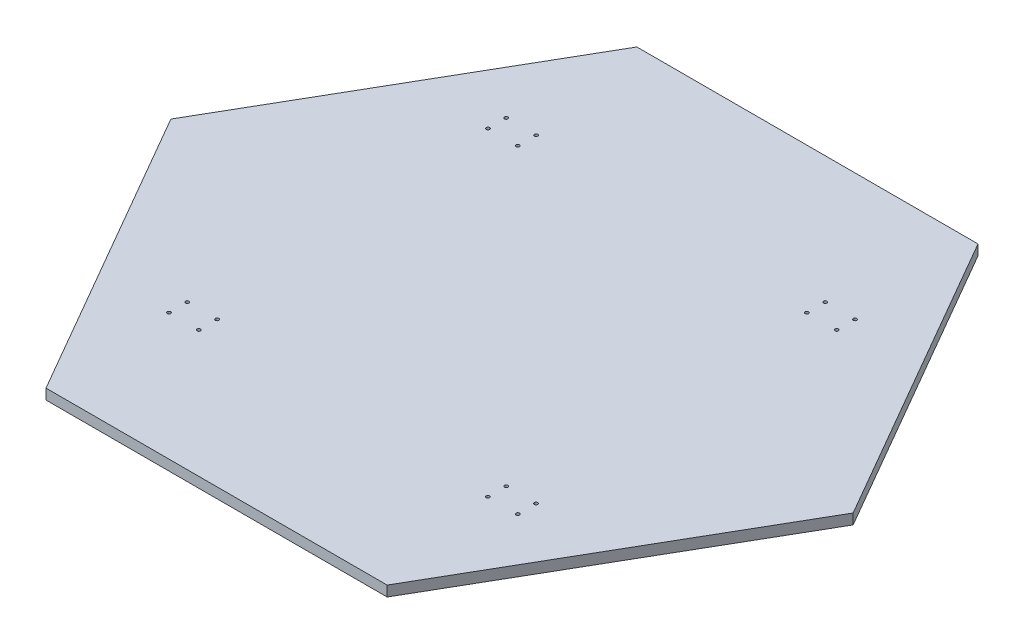
SolidWorks part; units mm, degrees
ref_plane "Front Plane" through (0, 0, 0) normal (0, 0, 1) x (1, 0, 0)
ref_plane "Top Plane" through (0, 0, 0) normal (0, 1, 0) x (1, 0, 0)
ref_plane "Right Plane" through (0, 0, 0) normal (1, 0, 0) x (0, 0, -1)
sketch "Sketch1" plane through (0, 0, 0) normal (0, 1, 0) x (1, 0, 0)
  line L38 (835.3235, 0) -> (417.6617, 723.4114)
  line L39 (417.6617, 723.4114) -> (-417.6617, 723.4114)
  line L40 (-417.6617, 723.4114) -> (-835.3235, 0)
  line L41 (-835.3235, 0) -> (-417.6617, -723.4114)
  line L42 (-417.6617, -723.4114) -> (417.6617, -723.4114)
  line L43 (417.6617, -723.4114) -> (835.3235, 0)
  line L44 (762, 0) -> (381, 659.9114)
  line L45 (381, 659.9114) -> (-381, 659.9114)
  line L46 (-381, 659.9114) -> (-762, 0)
  line L47 (-762, 0) -> (-381, -659.9114)
  line L48 (-381, -659.9114) -> (381, -659.9114)
  line L49 (381, -659.9114) -> (762, 0)
  line L50 (762, 0) -> (381, 659.9114) construction
  line L51 (381, 659.9114) -> (-381, 659.9114) construction
  line L52 (-381, 659.9114) -> (-762, 0) construction
  line L53 (-762, 0) -> (-381, -659.9114) construction
  line L54 (-381, -659.9114) -> (381, -659.9114) construction
  line L55 (381, -659.9114) -> (762, 0) construction
  point P1 (923.3117, 0)
  dimension "D1" = 0
  dimension "D2" = 63.5
extrude "Boss-Extrude1" add sketch "Sketch1" along normal blind 25.4
sketch "Sketch5" plane through (0, 25.4, 0) normal (0, 1, 0) x (1, 0, 0)
  line L0 (-390.525, 390.525) -> (390.525, 390.525) construction
  line L1 (-427.101, 412.877) -> (-353.949, 412.877) construction
  line L2 (-427.101, 412.877) -> (-427.101, 368.173) construction
  line L3 (-427.101, 368.173) -> (-353.949, 368.173) construction
  line L4 (-353.949, 412.877) -> (-353.949, 368.173) construction
  line L5 (-390.525, 390.525) -> (-390.525, -390.525) construction
  line L6 (0, 390.525) -> (0, 0) construction
  line L9 (-355.6, 412.877) -> (-352.298, 412.877) construction
  line L10 (-355.6, 417.068) -> (-352.298, 417.068) construction
  line L11 (-355.6, 408.686) -> (-352.298, 408.686) construction
  line L12 (0, 0) -> (390.525, 0) construction
  line L15 (355.6, 412.877) -> (352.298, 412.877) construction
  line L18 (355.6, 417.068) -> (352.298, 417.068) construction
  line L19 (355.6, 408.686) -> (352.298, 408.686) construction
  line L20 (353.949, 412.877) -> (353.949, 368.173) construction
  line L22 (427.101, 368.173) -> (353.949, 368.173) construction
  line L23 (390.525, 390.525) -> (-390.525, 390.525)
  line L24 (390.525, -390.525) -> (390.525, 390.525)
  line L25 (-390.525, -390.525) -> (390.525, -390.525)
  line L31 (-390.525, 390.525) -> (-390.525, -390.525)
  line L34 (390.525, 390.525) -> (-390.525, 390.525) construction
  line L37 (390.525, -390.525) -> (390.525, 390.525) construction
  line L44 (-390.525, -390.525) -> (390.525, -390.525) construction
  line L47 (-390.525, 390.525) -> (-390.525, -390.525) construction
  line L48 (427.101, 412.877) -> (427.101, 368.173) construction
  line L49 (427.101, 412.877) -> (353.949, 412.877) construction
  line L50 (-355.6, -412.877) -> (-352.298, -412.877) construction
  line L51 (-355.6, -417.068) -> (-352.298, -417.068) construction
  line L52 (-355.6, -408.686) -> (-352.298, -408.686) construction
  line L53 (355.6, -412.877) -> (352.298, -412.877) construction
  line L54 (355.6, -417.068) -> (352.298, -417.068) construction
  line L55 (355.6, -408.686) -> (352.298, -408.686) construction
  line L56 (427.101, -412.877) -> (353.949, -412.877) construction
  line L57 (427.101, -412.877) -> (427.101, -368.173) construction
  line L58 (390.525, -390.525) -> (-390.525, -390.525) construction
  line L59 (427.101, -368.173) -> (353.949, -368.173) construction
  line L60 (353.949, -412.877) -> (353.949, -368.173) construction
  line L61 (-353.949, -412.877) -> (-353.949, -368.173) construction
  line L62 (-427.101, -368.173) -> (-353.949, -368.173) construction
  line L63 (-427.101, -412.877) -> (-427.101, -368.173) construction
  line L64 (-427.101, -412.877) -> (-353.949, -412.877) construction
  arc A2 (-355.6, 417.068) -> (-355.6, 408.686) centre (-355.6, 412.877) ccw construction
  arc A3 (-352.298, 408.686) -> (-352.298, 417.068) centre (-352.298, 412.877) ccw construction
  circle A8 centre (-353.949, 412.877) radius 4.191
  circle A9 centre (-427.101, 412.877) radius 4.191
  circle A10 centre (-427.101, 368.173) radius 4.191
  circle A11 centre (-353.949, 368.173) radius 4.191
  arc A12 (355.6, 417.068) -> (355.6, 408.686) centre (355.6, 412.877) cw construction
  arc A13 (352.298, 408.686) -> (352.298, 417.068) centre (352.298, 412.877) cw construction
  circle A14 centre (353.949, 368.173) radius 4.191
  circle A15 centre (427.101, 368.173) radius 4.191
  circle A16 centre (427.101, 412.877) radius 4.191
  circle A17 centre (353.949, 412.877) radius 4.191
  arc A18 (-355.6, -417.068) -> (-355.6, -408.686) centre (-355.6, -412.877) cw construction
  arc A19 (-352.298, -408.686) -> (-352.298, -417.068) centre (-352.298, -412.877) cw construction
  arc A20 (355.6, -417.068) -> (355.6, -408.686) centre (355.6, -412.877) ccw construction
  arc A21 (352.298, -408.686) -> (352.298, -417.068) centre (352.298, -412.877) ccw construction
  circle A22 centre (353.949, -412.877) radius 4.191
  circle A23 centre (427.101, -412.877) radius 4.191
  circle A24 centre (427.101, -368.173) radius 4.191
  circle A25 centre (353.949, -368.173) radius 4.191
  circle A26 centre (-353.949, -368.173) radius 4.191
  circle A27 centre (-427.101, -368.173) radius 4.191
  circle A28 centre (-427.101, -412.877) radius 4.191
  circle A29 centre (-353.949, -412.877) radius 4.191
  point P4 (-390.525, 390.525)
  point P5 (-390.525, 412.877)
  point P6 (-353.949, 390.525)
  point P18 (-353.949, 412.877)
  point P27 (353.949, 412.877)
  point P45 (390.525, 390.525)
  point P48 (-353.949, -412.877)
  point P55 (353.949, -412.877)
  point P76 (390.525, -390.525)
  point P77 (-390.525, -390.525)
  dimension "D4" = 11.684
  dimension "D1" = 44.704
  dimension "D2" = 73.152
  dimension "D3" = 8.382
  dimension "D5" = 0
extrude "Cut-Extrude1" cut sketch "Sketch5" against normal up to surface (25.4 mm away) up to face at (0, 0, 0)
